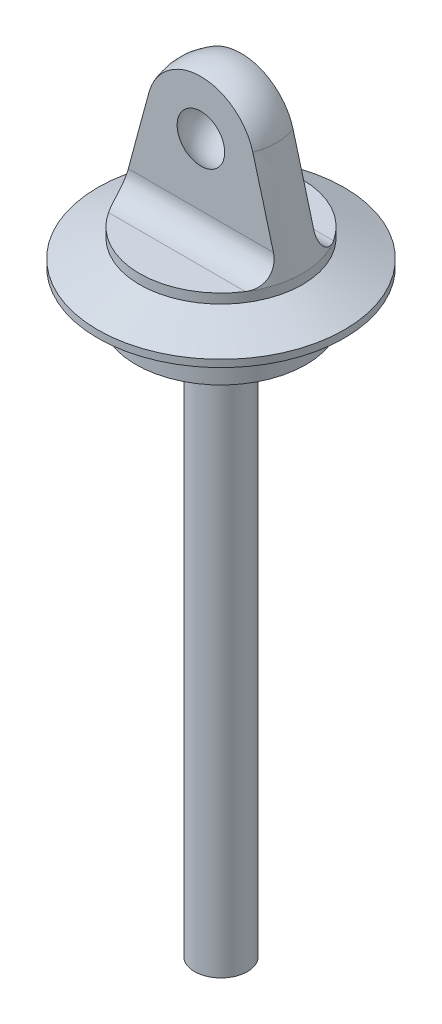
SolidWorks part; units mm, degrees
ref_plane "Front Plane" through (0, 0, 0) normal (0, 0, 1) x (1, 0, 0)
ref_plane "Top Plane" through (0, 0, 0) normal (0, 1, 0) x (1, 0, 0)
ref_plane "Right Plane" through (0, 0, 0) normal (1, 0, 0) x (0, 0, -1)
sketch "Sketch1" plane through (0, 0, 0) normal (0, 0, 1) x (1, 0, 0)
  line L0 (0, 0) -> (0, -150) construction
  line L1 (0, -150) -> (-5.5, -150)
  line L2 (-5.5, -150) -> (-5.5, -34.1)
  line L3 (-5.5, -34.1) -> (-17.75, -34.1)
  line L4 (-17.75, -34.1) -> (-17.75, -25.3)
  line L5 (-17.75, -25.3) -> (-25.75, -25.3)
  line L6 (-25.75, -25.3) -> (-25.75, -23.8)
  line L7 (-25.75, -23.8) -> (-17, -20)
  line L8 (-17, -20) -> (-17, -18)
  line L9 (-17, -18) -> (-11.6244, 2.9786)
  line L10 (0, 0) -> (0, 12) construction
  line L11 (0, -150) -> (0, 12)
  arc A0 (0, 12) -> (-11.6244, 2.9786) centre (0, 0) ccw
  dimension "D3" = 24
  dimension "D2" = 150
  dimension "D4" = 17
  dimension "D5" = 25.75
  dimension "D6" = 2
  dimension "D7" = 18
  dimension "D8" = 8
  dimension "D9" = 1.5
  dimension "D10" = 8.8
  dimension "D11" = 3.8
  dimension "D12" = 5.5
revolve "Revolve1" add sketch "Sketch1" angle 360 about L11
sketch "Sketch2" plane through (0, 0, 0) normal (1, 0, 0) x (0, 0, -1)
  line L0 (0, 12) -> (0, -18) construction
  line L1 (-17, -18) -> (17, -18) construction
  line L2 (-4.2, 12.4342) -> (-4.2, -13)
  line L3 (-9.2, -18) -> (-21.1079, -18)
  line L4 (-21.1079, -18) -> (-21.1079, 12.4342)
  line L5 (-21.1079, 12.4342) -> (-4.2, 12.4342)
  line L6 (21.1079, 12.4342) -> (4.2, 12.4342)
  line L7 (21.1079, -18) -> (21.1079, 12.4342)
  line L8 (9.2, -18) -> (21.1079, -18)
  line L9 (4.2, 12.4342) -> (4.2, -13)
  arc A0 (11.6244, 2.9786) -> (-11.6244, 2.9786) centre (0, 0) ccw construction
  arc A1 (9.2, -18) -> (4.2, -13) centre (9.2, -13) cw
  arc A2 (-4.2, -13) -> (-9.2, -18) centre (-9.2, -13) cw
  point P17 (4.2, -18)
  point P20 (-4.2, -18)
  dimension "D2" = 5
  dimension "D1" = 4.2
extrude "Cut-Extrude1" cut sketch "Sketch2" against normal mid plane 50
sketch "Sketch3" plane through (0, 0, 0) normal (0, 0, 1) x (1, 0, 0)
  line L0 (0, -6.5) -> (0, 6.5) construction
  line L1 (0, -6.5) -> (0, 6.5)
  arc A0 (0, 6.5) -> (0, -6.5) centre (0, 0) ccw
  dimension "D1" = 13
revolve "Cut-Revolve1" cut sketch "Sketch3" angle 360 about L0
